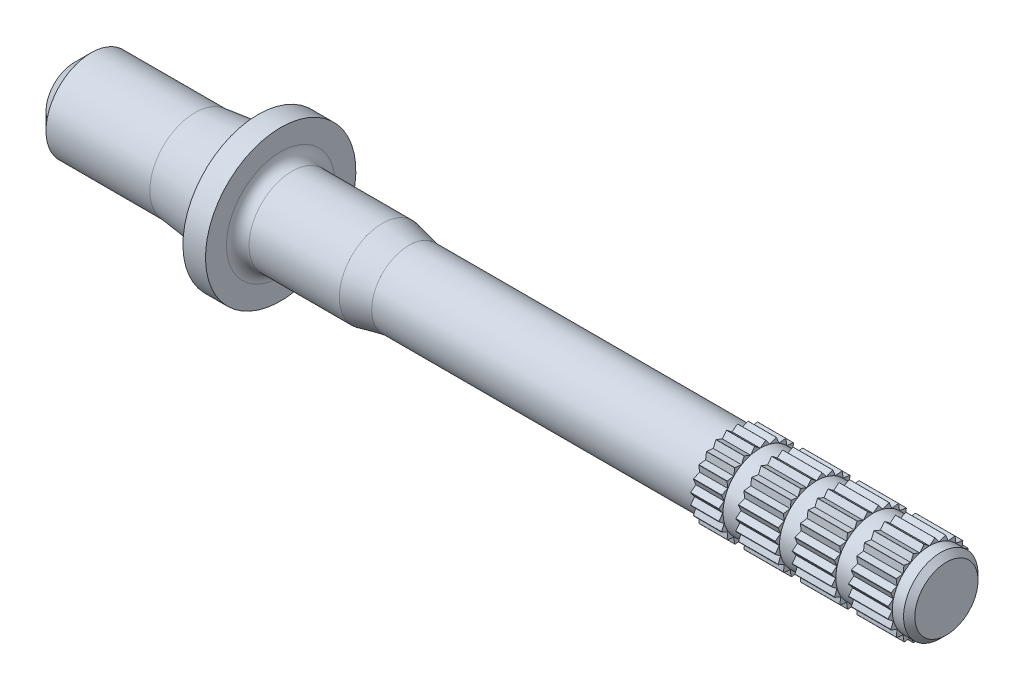
SolidWorks part; units mm, degrees
ref_plane "Front Plane" through (0, 0, 0) normal (0, 0, 1) x (1, 0, 0)
ref_plane "Top Plane" through (0, 0, 0) normal (0, 1, 0) x (1, 0, 0)
ref_plane "Right Plane" through (0, 0, 0) normal (1, 0, 0) x (0, 0, -1)
sketch "Sketch1" plane through (0, 0, 0) normal (0, 0, 1) x (1, 0, 0)
  line L0 (0, 0) -> (0, 2)
  line L1 (0, 2) -> (5.35, 2)
  line L2 (5.35, 2) -> (8.15, 2.3314)
  line L3 (8.15, 2.3314) -> (8.15, 3.3314)
  line L4 (8.15, 3.3314) -> (9.15, 3.3314)
  line L5 (9.15, 3.3314) -> (9.15, 1.9014)
  line L6 (9.15, 1.9014) -> (13.65, 1.9014)
  line L7 (13.65, 1.9014) -> (14.8328, 1.65)
  line L8 (14.8328, 1.65) -> (29.1528, 1.65)
  line L9 (29.1528, 1.65) -> (29.1528, 1.85)
  line L10 (29.1528, 1.85) -> (38.6528, 1.85)
  line L11 (38.6528, 1.85) -> (38.6528, 0)
  line L12 (38.6528, 0) -> (0, 0)
  dimension "D1" = 173.25
  dimension "D2" = 2
  dimension "D3" = 5.35
  dimension "D4" = 168
  dimension "D5" = 1.43
  dimension "D6" = 1
  dimension "D7" = 14.32
  dimension "D8" = 4.5
  dimension "D9" = 1
  dimension "D10" = 2.8
  dimension "D11" = 0.2
  dimension "D12" = 9.5
  dimension "D13" = 1.85
revolve "Revolve1" add sketch "Sketch1" angle 360 about L12
sketch "Sketch2" plane through (38.6528, 0, 0) normal (1, 0, 0) x (0, 0, -1)
  line L0 (0, 0) -> (0, 1.85) construction
  line L1 (-0.2402, 1.8343) -> (0, 1.65)
  line L2 (0, 1.65) -> (0.2402, 1.8343)
  circle A0 centre (0, 0) radius 1.85 construction
  circle A1 centre (0, 0) radius 1.65 construction
  arc A2 (-0.2402, 1.8343) -> (0.2402, 1.8343) centre (0, 0) cw
  dimension "D1" = 105
extrude "Cut-Extrude1" cut sketch "Sketch2" against normal up to next
pattern_circular "CirPattern1" count 24 over 360 about axis through (0, -0.0082, 0) along (1, 0, 0) of "Cut-Extrude1"
sketch "Sketch5" plane through (38.6528, 0, 0) normal (1, 0, 0) x (0, 0, -1)
  circle A0 centre (0, 0) radius 1.65
extrude "Cut-Extrude4" cut sketch "Sketch5" against normal blind 0.75 flip side to cut
pattern_linear "LPattern1" count 4 spacing 2.5 along (-1, 0, 0) of "Cut-Extrude4"
chamfer "Chamfer1" distance 0.25 angle 45 1 edges at (38.6528, 1.65, 0)
chamfer "Chamfer2" distance 0.75 angle 45 1 edges at (0, 2, 0)
fillet "Fillet1" radius 0.5 2 edges at (9.15, 1.9014, 0) (8.15, 2.3314, 0)
